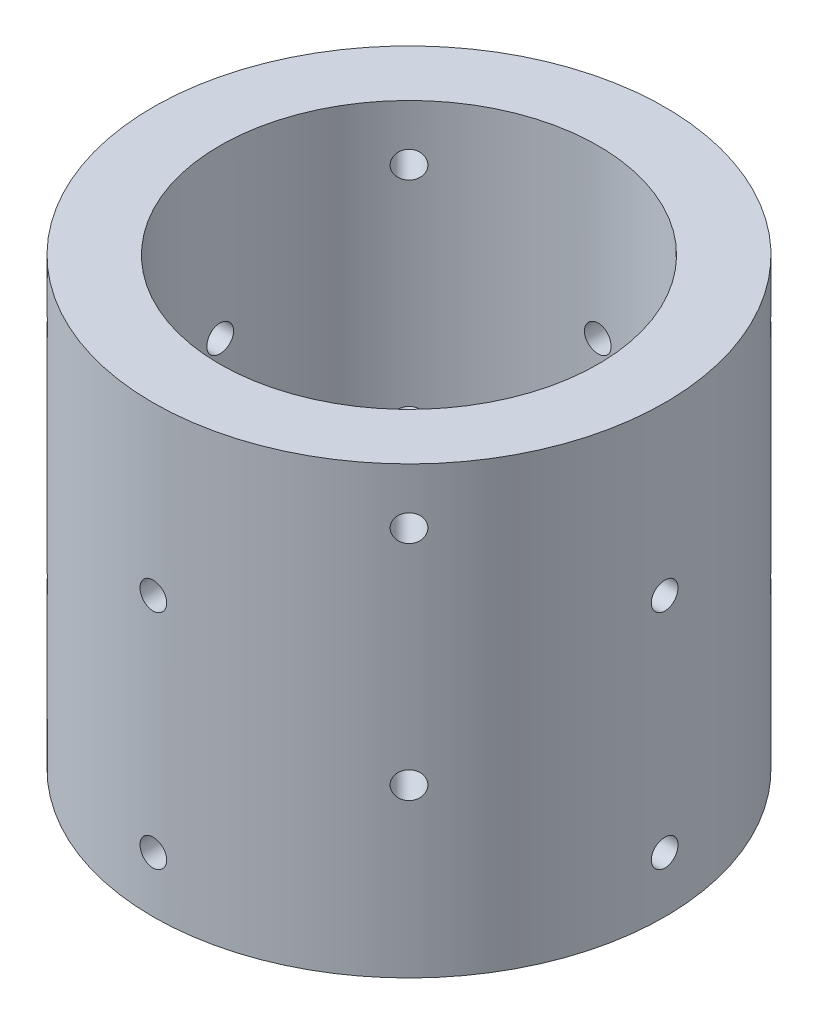
SolidWorks part; units mm, degrees
material "PLA плотность"
ref_plane "Спереди" through (0, 0, 0) normal (0, 0, 1) x (1, 0, 0)
ref_plane "Сверху" through (0, 0, 0) normal (0, 1, 0) x (1, 0, 0)
ref_plane "Справа" through (0, 0, 0) normal (1, 0, 0) x (0, 0, -1)
sketch "Эскиз1" plane through (0, 0, 0) normal (0, 1, 0) x (1, 0, 0)
  circle A0 centre (0, 0) radius 23
  dimension "D1" = 46
extrude "Бобышка-Вытянуть1" add sketch "Эскиз1" along normal blind 10
sketch "Эскиз2" plane through (0, 10, 0) normal (0, 1, 0) x (1, 0, 0)
  circle A0 centre (0, 0) radius 23
  circle A1 centre (0, 0) radius 17
  circle A2 centre (0, 0) radius 23 construction
  dimension "D1" = 34
  dimension "D2" = 0
extrude "Бобышка-Вытянуть2" add sketch "Эскиз2" along normal blind 30
sketch "Эскиз3" plane through (0, 0, 0) normal (1, 0, 0) x (0, 0, -1)
  line L0 (-23, 20) -> (30.2453, 20) construction
  line L1 (-23, 40) -> (-23, 0) construction
  line L2 (0, 25) -> (0, -3.082) construction
  line L3 (17, 40) -> (-17, 40) construction
  line L4 (-23, 0) -> (23, 0) construction
  circle A0 centre (0, 25) radius 1.2
  circle A2 centre (0, 5) radius 1.2
  dimension "D1" = 2.4
  dimension "D3" = 5
  dimension "D4" = 2.4
  dimension "D2" = 15
extrude "Вырез-Вытянуть1" cut sketch "Эскиз3" against normal through all from offset 16.8 offset against normal yes
ref_plane "Плоскость1" through (0, 0, 0) normal (0.7071, 0, 0.7071) x (0, -1, 0)
sketch "Эскиз4" plane through (0, 0, 0) normal (0.7071, 0, 0.7071) x (0, -1, 0)
  line L0 (-20, 23) -> (-20, -29.9249) construction
  line L1 (0, 23) -> (-40, 23) construction
  line L2 (-40, 0) -> (0, 0) construction
  line L3 (0, -23) -> (0, 23) construction
  line L4 (-40, 23) -> (-40, -23) construction
  circle A0 centre (-15, 0) radius 1.2
  circle A2 centre (-35, 0) radius 1.2
  dimension "D1" = 2.4
  dimension "D3" = 2.4
  dimension "D2" = 15
  dimension "D4" = 5
extrude "Вырез-Вытянуть2" cut sketch "Эскиз4" against normal through all
pattern_circular "Круговой массив1" count 4 over 360 about axis through (0, 0, 0) along (0, 1, 0) of "Вырез-Вытянуть1"
pattern_circular "Круговой массив2" count 4 over 360 about axis through (0, 10, 0) along (0, -1, 0) of "Вырез-Вытянуть2"
